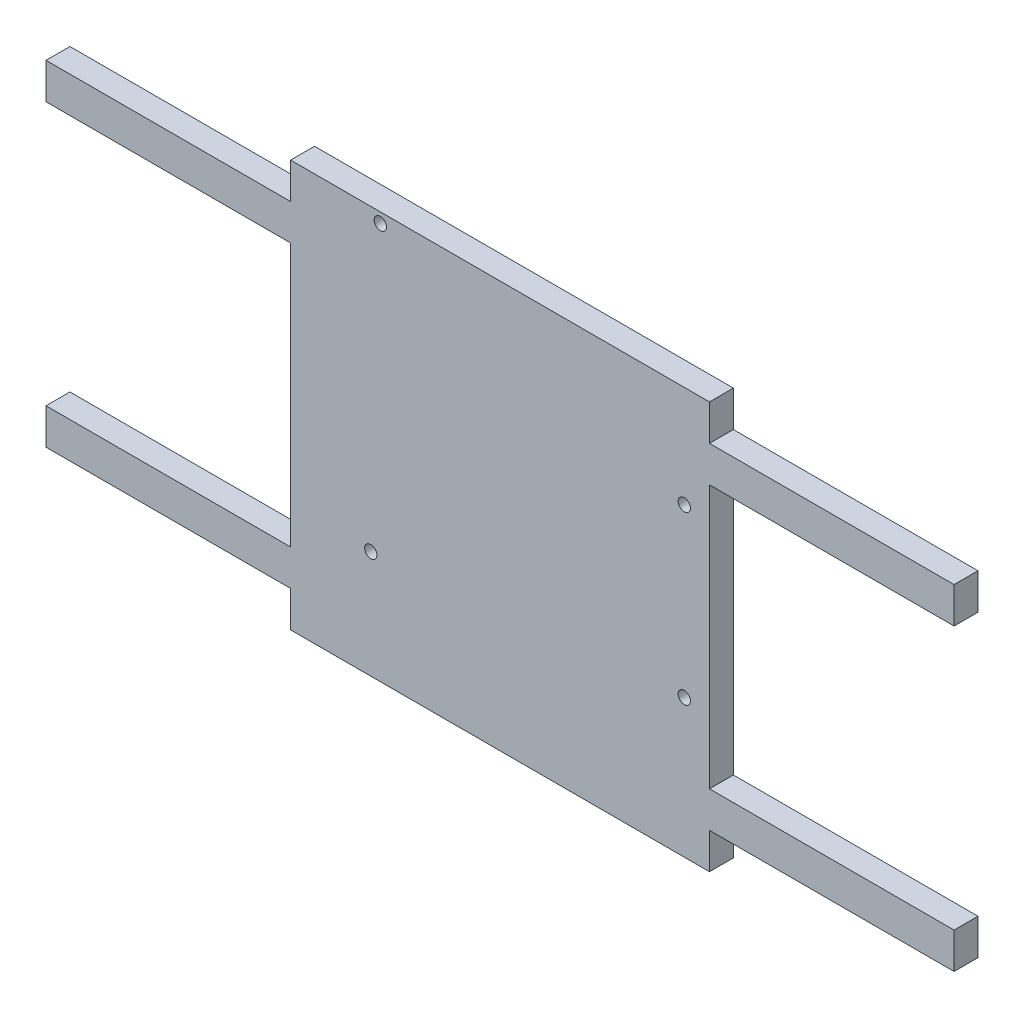
SolidWorks part; units mm, degrees
ref_plane "Front Plane" through (0, 0, 0) normal (0, 0, 1) x (1, 0, 0)
ref_plane "Top Plane" through (0, 0, 0) normal (0, 1, 0) x (1, 0, 0)
ref_plane "Right Plane" through (0, 0, 0) normal (1, 0, 0) x (0, 0, -1)
sketch "Sketch1" plane through (0, 0, 0) normal (0, 0, 1) x (1, 0, 0)
  line L0 (0, 34) -> (0, -34) construction
  line L1 (-35, 34) -> (35, 34)
  line L2 (-35, 34) -> (-35, -34)
  line L3 (-35, -34) -> (35, -34)
  line L4 (35, 34) -> (35, -34)
  line L5 (-35, 0) -> (35, 0) construction
  circle A0 centre (-21.6065, -15.9783) radius 1.0287
  circle A1 centre (30.7935, -10.8783) radius 1.0287
  circle A2 centre (30.7935, 17.0217) radius 1.0287
  circle A3 centre (-20.0065, 32.3217) radius 1.0287
  dimension "D1" = 68
  dimension "D2" = 70
extrude "Boss-Extrude1" add sketch "Sketch1" along normal blind 4
sketch "Sketch2" plane through (0, 0, 0) normal (0, 0, -1) x (-1, 0, 0)
  line L0 (35, 34) -> (35, -34) construction
  line L1 (35, 28) -> (75.88, 28)
  line L2 (35, 28) -> (35, 22)
  line L3 (35, 22) -> (75.88, 22)
  line L4 (75.88, 28) -> (75.88, 22)
  line L5 (-35, 34) -> (35, 34) construction
  line L6 (0, 34) -> (0, -34) construction
  line L7 (35, -34) -> (-35, -34) construction
  line L8 (-35, 0) -> (35, 0) construction
  line L9 (-35, -34) -> (-35, 34) construction
  line L10 (-75.88, 28) -> (-75.88, 22)
  line L11 (-35, 22) -> (-75.88, 22)
  line L12 (-35, 28) -> (-35, 22)
  line L13 (-35, 28) -> (-75.88, 28)
  line L14 (-35, -28) -> (-35, -22)
  line L15 (-35, -22) -> (-75.88, -22)
  line L16 (-75.88, -28) -> (-75.88, -22)
  line L17 (-35, -28) -> (-75.88, -28)
  line L18 (75.88, -28) -> (75.88, -22)
  line L19 (35, -22) -> (75.88, -22)
  line L20 (35, -28) -> (35, -22)
  line L21 (35, -28) -> (75.88, -28)
  dimension "D1" = 40.88
  dimension "D2" = 6
  dimension "D3" = 44
extrude "Boss-Extrude2" add sketch "Sketch2" against normal blind 4
